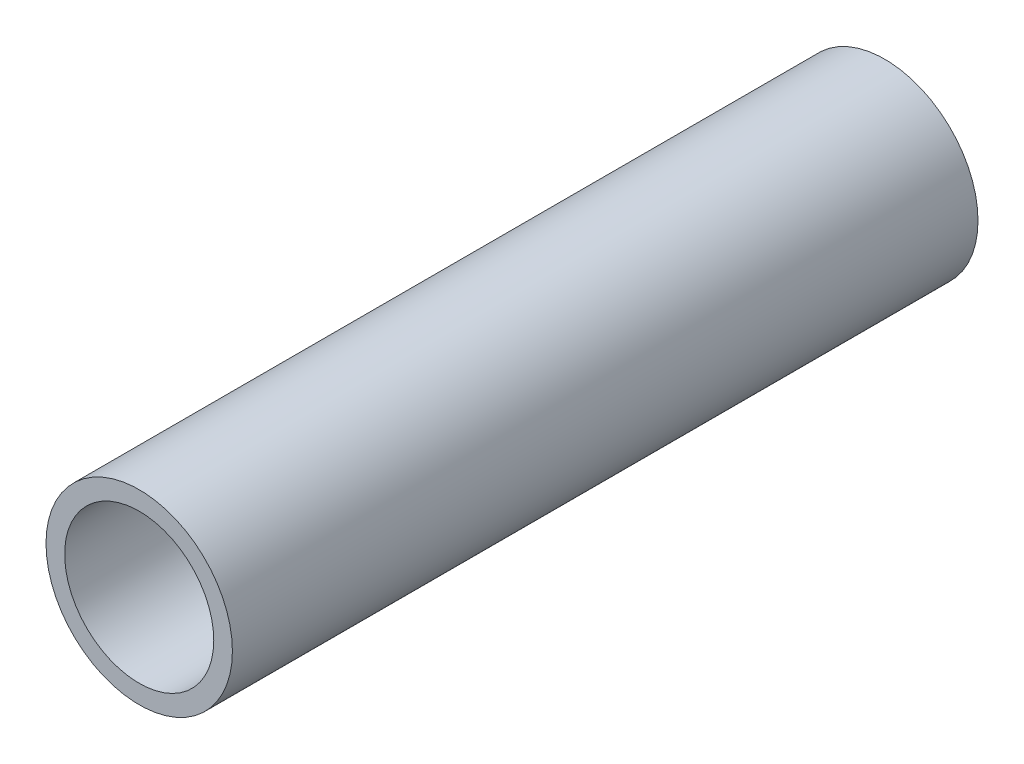
SolidWorks part; units mm, degrees
ref_plane "Front Plane" through (0, 0, 0) normal (0, 0, 1) x (1, 0, 0)
ref_plane "Top Plane" through (0, 0, 0) normal (0, 1, 0) x (1, 0, 0)
ref_plane "Right Plane" through (0, 0, 0) normal (1, 0, 0) x (0, 0, -1)
sketch "Sketch1" plane through (0, 0, 0) normal (0, 0, 1) x (1, 0, 0)
  circle A0 centre (0, 0) radius 25
  circle A1 centre (0, 0) radius 20
  dimension "D1" = 50
  dimension "D2" = 40
extrude "Boss-Extrude1" add sketch "Sketch1" along normal blind 200
